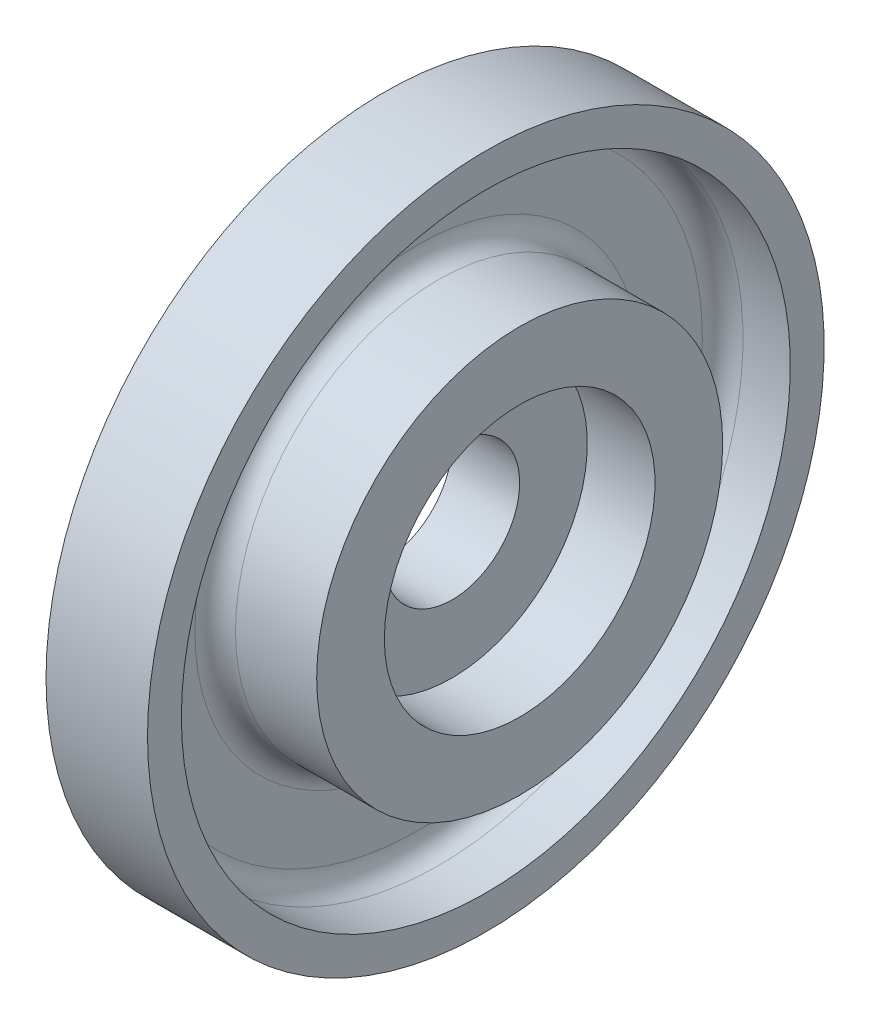
SolidWorks part; units mm, degrees
ref_plane "Alzado" through (0, 0, 0) normal (0, 0, 1) x (1, 0, 0)
ref_plane "Planta" through (0, 0, 0) normal (0, 1, 0) x (1, 0, 0)
ref_plane "Vista lateral" through (0, 0, 0) normal (1, 0, 0) x (0, 0, -1)
sketch "Croquis1" plane through (0, 0, 0) normal (0, 0, 1) x (1, 0, 0)
  line L0 (0, 10) -> (0, 50)
  line L1 (0, 50) -> (15, 50)
  line L2 (15, 50) -> (15, 45)
  line L3 (15, 45) -> (8, 45)
  line L4 (5, 42) -> (5, 33)
  line L5 (8, 30) -> (20, 30)
  line L6 (20, 30) -> (20, 20)
  line L7 (20, 20) -> (10, 20)
  line L8 (10, 20) -> (10, 10)
  line L9 (10, 10) -> (0, 10)
  line L10 (-16.4848, 0) -> (25.67, 0) construction
  arc A0 (8, 45) -> (5, 42) centre (8, 42) ccw
  arc A1 (5, 33) -> (8, 30) centre (8, 33) ccw
  dimension "D9" = 3
  dimension "D1" = 15
  dimension "D2" = 20
  dimension "D3" = 10
  dimension "D4" = 10
  dimension "D5" = 20
  dimension "D6" = 30
  dimension "D7" = 45
  dimension "D8" = 50
  dimension "D10" = 10
revolve "Revolución1" add sketch "Croquis1" angle 360 about L10
